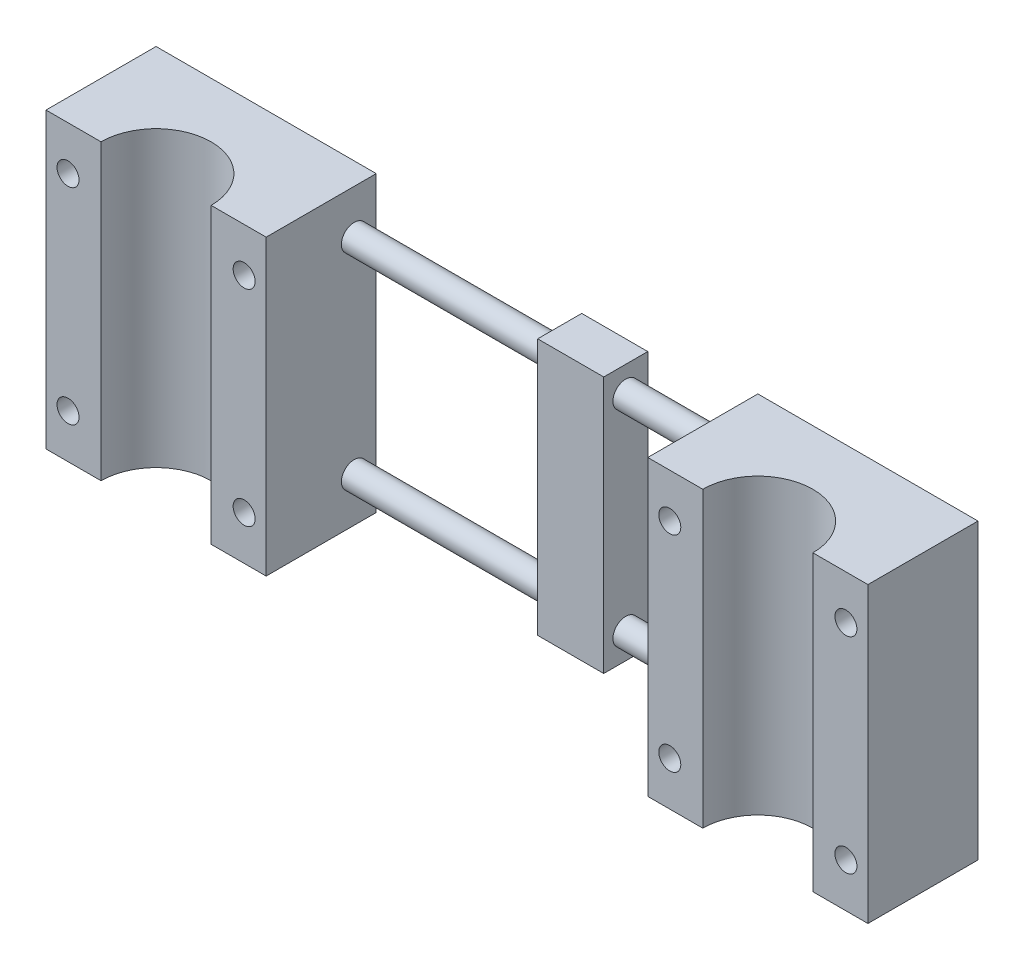
SolidWorks part; units mm, degrees
ref_plane "Front Plane" through (0, 0, 0) normal (0, 0, 1) x (1, 0, 0)
ref_plane "Top Plane" through (0, 0, 0) normal (0, 1, 0) x (1, 0, 0)
ref_plane "Right Plane" through (0, 0, 0) normal (1, 0, 0) x (0, 0, -1)
sketch "Sketch1" plane through (0, 0, 0) normal (0, 0, 1) x (1, 0, 0)
  line L1 (0, 0) -> (30, 0)
  line L2 (0, 0) -> (0, 40)
  line L3 (0, 40) -> (30, 40)
  line L4 (30, 0) -> (30, 40)
  dimension "D1" = 40
  dimension "D2" = 30
extrude "Boss-Extrude1" add sketch "Sketch1" along normal blind 15
sketch "Sketch2" plane through (0, 40, 0) normal (0, 1, 0) x (1, 0, 0)
  line L0 (30, -15) -> (0, -15) construction
  line L1 (7.5, -15) -> (22.5, -15)
  arc A0 (22.5, -15) -> (7.5, -15) centre (15, -15) ccw
  dimension "D1" = 15
extrude "Cut-Extrude1" cut sketch "Sketch2" against normal blind 49
sketch "Sketch3" plane through (0, 0, 15) normal (0, 0, 1) x (1, 0, 0)
  line L0 (7.5, 40) -> (0, 40) construction
  line L1 (0, 40) -> (0, 0) construction
  line L2 (30, 0) -> (30, 40) construction
  line L3 (30, 40) -> (22.5, 40) construction
  line L4 (22.5, 0) -> (30, 0) construction
  line L5 (0, 0) -> (7.5, 0) construction
  circle A0 centre (3, 34) radius 1.5
  circle A1 centre (3, 6) radius 1.5
  circle A2 centre (27, 34) radius 1.5
  circle A3 centre (27, 6) radius 1.5
  point P19 (26.25, 0)
  point P25 (3.75, 0)
  dimension "D1" = 3
  dimension "D2" = 3
  dimension "D3" = 3
  dimension "D4" = 3
  dimension "D5" = 6
  dimension "D6" = 3
  dimension "D7" = 3
  dimension "D8" = 6
  dimension "D9" = 6
  dimension "D10" = 3
  dimension "D11" = 3
  dimension "D12" = 6
extrude "Cut-Extrude2" cut sketch "Sketch3" against normal blind 49
sketch "Sketch4" plane through (30, 0, 0) normal (1, 0, 0) x (0, 0, -1)
  line L0 (-15, 40) -> (0, 40) construction
  line L1 (-15, 0) -> (0, 0) construction
  line L2 (0, 0) -> (0, 40) construction
  circle A0 centre (-3, 34) radius 1.75
  circle A1 centre (-3, 6) radius 1.75
  dimension "D1" = 3.5
  dimension "D2" = 3.5
  dimension "D3" = 6
  dimension "D4" = 6
  dimension "D5" = 3
  dimension "D6" = 3
extrude "Boss-Extrude2" add sketch "Sketch4" along normal blind 28
sketch "Sketch5" plane through (58, 0, 0) normal (1, 0, 0) x (0, 0, -1)
  line L0 (0, 0) -> (0, 40) construction
  line L1 (0, 37.5) -> (-6, 37.5)
  line L2 (0, 37.5) -> (0, 2.5)
  line L3 (0, 2.5) -> (-6, 2.5)
  line L4 (-6, 37.5) -> (-6, 2.5)
  circle A0 centre (-3, 34) radius 1.75 construction
  point P6 (-3, 37.5)
  dimension "D3" = 6
  dimension "D1" = 3.5
  dimension "D2" = 35
extrude "Boss-Extrude3" add sketch "Sketch5" along normal blind 9
sketch "Sketch6" plane through (67, 0, 0) normal (1, 0, 0) x (0, 0, -1)
  line L0 (-15, 0) -> (0, 0) construction
  line L3 (0, 0) -> (0, 40) construction
  line L4 (-15, 40) -> (0, 40) construction
  circle A0 centre (-3, 34) radius 1.75
  circle A1 centre (-3, 6) radius 1.75
  dimension "D1" = 3.5
  dimension "D2" = 3.5
  dimension "D3" = 3
  dimension "D4" = 6
  dimension "D5" = 6
extrude "Boss-Extrude4" add sketch "Sketch6" along normal blind 15
sketch "Sketch7" plane through (82, 0, 0) normal (1, 0, 0) x (0, 0, -1)
  line L1 (0, 40) -> (-15, 40)
  line L2 (0, 40) -> (0, 0)
  line L3 (0, 0) -> (-15, 0)
  line L4 (-15, 40) -> (-15, 0)
extrude "Boss-Extrude6" add sketch "Sketch7" along normal blind 30
sketch "Sketch9" plane through (0, 40, 0) normal (0, 1, 0) x (1, 0, 0)
  line L0 (112, -15) -> (82, -15) construction
  line L1 (89.5, -15) -> (104.5, -15)
  arc A0 (104.5, -15) -> (89.5, -15) centre (97, -15) ccw
  dimension "D1" = 15
extrude "Cut-Extrude3" cut sketch "Sketch9" against normal blind 59
sketch "Sketch10" plane through (0, 0, 15) normal (0, 0, 1) x (1, 0, 0)
  line L0 (89.5, 40) -> (82, 40) construction
  line L1 (82, 40) -> (82, 0) construction
  line L2 (112, 40) -> (112, 0) construction
  line L3 (112, 40) -> (104.5, 40) construction
  line L4 (112, 0) -> (104.5, 0) construction
  line L5 (89.5, 0) -> (82, 0) construction
  circle A0 centre (85, 34) radius 1.5
  circle A1 centre (109, 34) radius 1.5
  circle A2 centre (109, 6) radius 1.5
  circle A3 centre (85, 6) radius 1.5
  dimension "D1" = 3
  dimension "D2" = 6
  dimension "D3" = 3
  dimension "D4" = 3
  dimension "D5" = 6
  dimension "D6" = 3
  dimension "D7" = 6
  dimension "D8" = 6
  dimension "D9" = 3
extrude "Cut-Extrude4" cut sketch "Sketch10" against normal blind 59
ref_plane "Plane1" through (56, 0, 0) normal (1, 0, 0) x (0, 0, -1)
